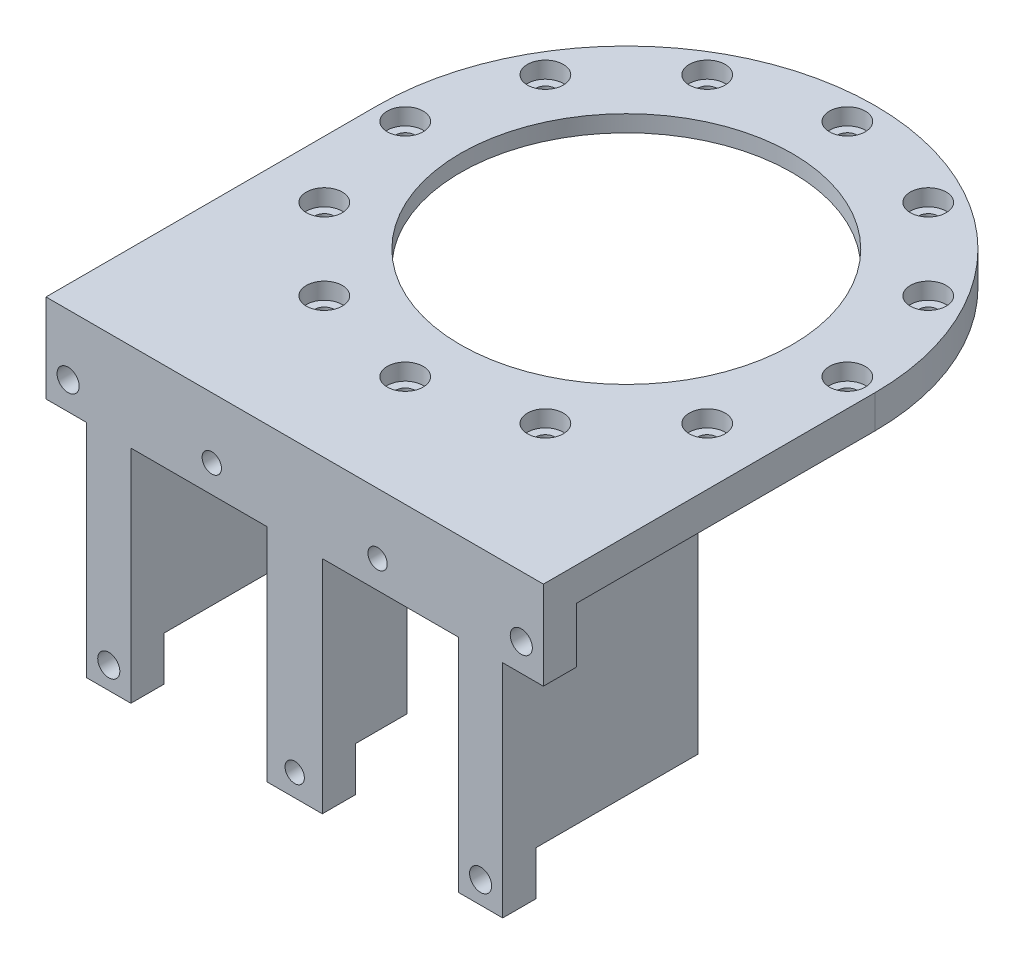
SolidWorks part; units mm, degrees
ref_plane "Front Plane" through (0, 0, 0) normal (0, 0, 1) x (1, 0, 0)
ref_plane "Top Plane" through (0, 0, 0) normal (0, 1, 0) x (1, 0, 0)
ref_plane "Right Plane" through (0, 0, 0) normal (1, 0, 0) x (0, 0, -1)
sketch "Sketch1" plane through (0, 0, 0) normal (0, 1, 0) x (1, 0, 0)
  line L0 (0, 0) -> (0, 52.0165) construction
  circle A0 centre (0, 0) radius 45
  circle A1 centre (0, 0) radius 30
  circle A2 centre (0, 0) radius 40 construction
  circle A3 centre (0, 40) radius 1.75
  circle A4 centre (0, 0) radius 36 construction
  circle A5 centre (20, 34.641) radius 1.75
  circle A6 centre (34.641, 20) radius 1.75
  circle A7 centre (40, 0) radius 1.75
  circle A8 centre (34.641, -20) radius 1.75
  circle A9 centre (20, -34.641) radius 1.75
  circle A10 centre (0, -40) radius 1.75
  circle A11 centre (-20, -34.641) radius 1.75
  circle A12 centre (-34.641, -20) radius 1.75
  circle A13 centre (-40, 0) radius 1.75
  circle A14 centre (-34.641, 20) radius 1.75
  circle A15 centre (-20, 34.641) radius 1.75
  point P21 (0, 0)
  point P34 (0, 0)
  point P48 (0, 0)
  point P72 (0, 0)
  dimension "D1" = 90
  dimension "D2" = 60
  dimension "D4" = 3.5
  dimension "D5" = 72
  dimension "D6" = 12
  dimension "D3" = 80
extrude "Boss-Extrude1" add sketch "Sketch1" along normal blind 6
sketch "Sketch2" plane through (0, 0, 0) normal (0, -1, 0) x (1, 0, 0)
  circle A0 centre (0, 0) radius 36
  dimension "D1" = 72
extrude "Cut-Extrude1" cut sketch "Sketch2" against normal blind 3
sketch "Sketch3" plane through (0, 6, 0) normal (0, 1, 0) x (1, 0, 0)
  line L0 (0, 0) -> (49.8808, 0) construction
  circle A0 centre (40, 0) radius 3.25
  circle A1 centre (34.641, -20) radius 3.25
  circle A2 centre (20, -34.641) radius 3.25
  circle A3 centre (0, -40) radius 3.25
  circle A4 centre (-20, -34.641) radius 3.25
  circle A5 centre (-34.641, -20) radius 3.25
  circle A6 centre (-40, 0) radius 3.25
  circle A7 centre (-34.641, 20) radius 3.25
  circle A8 centre (-20, 34.641) radius 3.25
  circle A9 centre (0, 40) radius 3.25
  circle A10 centre (20, 34.641) radius 3.25
  circle A11 centre (34.641, 20) radius 3.25
  point P30 (0, 0)
  dimension "D1" = 6.5
  dimension "D2" = 12
extrude "Cut-Extrude2" cut sketch "Sketch3" against normal blind 3
sketch "Sketch4" plane through (0, 0, 0) normal (0, -1, 0) x (1, 0, 0)
  line L0 (45, 0) -> (45, 60)
  line L1 (-45, 0) -> (-45, 60)
  line L2 (45, 60) -> (-45, 60)
  line L3 (45, 0) -> (-45, 0) construction
  circle A1 centre (0, 0) radius 45 construction
  arc A2 (45, 0) -> (-45, 0) centre (0, 0) ccw
  dimension "D1" = 60
  dimension "D2" = 90
extrude "Boss-Extrude4" add sketch "Sketch4" against normal blind 6
sketch "Sketch5" plane through (0, 0, 0) normal (0, -1, 0) x (1, 0, 0)
  line L0 (45, 0) -> (45, 60) construction
  line L1 (45, 54) -> (-45, 54)
  line L2 (45, 54) -> (45, 60)
  line L3 (45, 60) -> (-45, 60)
  line L4 (-45, 54) -> (-45, 60)
  dimension "D1" = 6
extrude "Boss-Extrude6" add sketch "Sketch5" along normal blind 10
sketch "Sketch6" plane through (0, 0, 0) normal (0, -1, 0) x (1, 0, 0)
  line L0 (0, 0) -> (0, 68.4249) construction
  line L1 (34.641, 20) -> (34.641, 68.4249) construction
  line L2 (37.641, 24.6608) -> (37.641, 60)
  line L3 (45, 60) -> (-45, 60) construction
  line L4 (37.641, 60) -> (29.641, 60)
  line L5 (29.641, 60) -> (29.641, 33.8587)
  line L6 (-5, 60) -> (5, 60)
  line L7 (5, 60) -> (5, 44.7214)
  line L8 (-5, 60) -> (-5, 44.7214)
  line L9 (-29.641, 60) -> (-29.641, 33.8587)
  line L10 (-37.641, 60) -> (-29.641, 60)
  line L11 (-37.641, 24.6608) -> (-37.641, 60)
  arc A0 (37.641, 24.6608) -> (29.641, 33.8587) centre (0, 0) ccw
  arc A1 (5, 44.7214) -> (-5, 44.7214) centre (0, 0) ccw
  arc A2 (-37.641, 24.6608) -> (-29.641, 33.8587) centre (0, 0) cw
  point P17 (0, 60)
  dimension "D1" = 90
  dimension "D2" = 3
  dimension "D3" = 5
  dimension "D4" = 5
extrude "Boss-Extrude7" add sketch "Sketch6" along normal blind 50
sketch "Sketch7" plane through (37.641, 0, 0) normal (1, 0, 0) x (0, 0, -1)
  line L0 (-24.6608, -42) -> (-54, -42)
  line L1 (-24.6608, -50) -> (-24.6608, 0) construction
  line L2 (-54, -42) -> (-54, -50)
  line L3 (-24.6608, -50) -> (-60, -50) construction
  line L4 (-60, -50) -> (-60, -10) construction
  line L5 (-24.6608, -42) -> (-24.6608, -50)
  line L6 (-24.6608, -50) -> (-54, -50)
  dimension "D1" = 6
  dimension "D2" = 8
extrude "Cut-Extrude3" cut sketch "Sketch7" against normal through all
sketch "Sketch8" plane through (0, 0, 54) normal (0, 0, -1) x (-1, 0, 0)
  line L0 (45, -5) -> (-45, -5) construction
  line L1 (45, -10) -> (45, 0) construction
  line L2 (-45, -10) -> (-45, 0) construction
  line L3 (33.641, -50) -> (33.641, -42) construction
  line L4 (37.641, -50) -> (29.641, -50) construction
  line L5 (37.641, -42) -> (29.641, -42) construction
  line L6 (0, -50) -> (0, -42) construction
  line L7 (5, -50) -> (-5, -50) construction
  line L8 (5, -42) -> (-5, -42) construction
  line L9 (-33.641, -50) -> (-33.641, -42) construction
  line L10 (-29.641, -50) -> (-37.641, -50) construction
  line L11 (-37.641, -42) -> (-29.641, -42) construction
  circle A0 centre (41, -5) radius 2
  circle A1 centre (33.641, -46) radius 2
  circle A2 centre (0, -46) radius 1.75
  circle A3 centre (15, -5) radius 1.75
  circle A4 centre (-33.641, -46) radius 2
  circle A5 centre (-41, -5) radius 2
  circle A6 centre (-15, -5) radius 1.75
  point P32 (0, -5)
  dimension "D1" = 4
  dimension "D3" = 4
  dimension "D5" = 3.5
  dimension "D7" = 3.5
  dimension "D2" = 4
  dimension "D4" = 4
  dimension "D6" = 4
  dimension "D8" = 15
extrude "Cut-Extrude5" cut sketch "Sketch8" against normal through all
